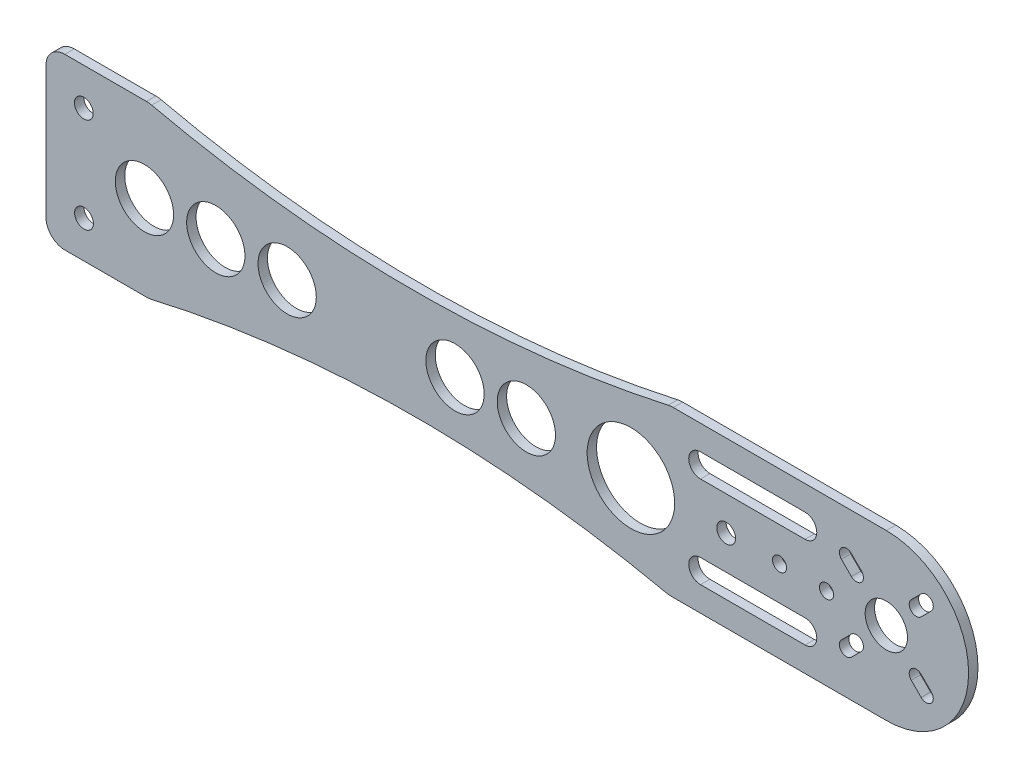
SolidWorks part; units mm, degrees
ref_plane "Alzado" through (0, 0, 0) normal (0, 0, 1) x (1, 0, 0)
ref_plane "Planta" through (0, 0, 0) normal (0, 1, 0) x (1, 0, 0)
ref_plane "Vista lateral" through (0, 0, 0) normal (1, 0, 0) x (0, 0, -1)
sketch "Croquis1" plane through (0, 0, 0) normal (0, 0, 1) x (1, 0, 0)
  line L0 (2814.9766, 1239.0428) -> (2832.3419, 1239.0428)
  line L1 (2814.9766, 1202.994) -> (2832.3207, 1202.994)
  line L2 (2982.2896, 1215.8859) -> (2980.1683, 1213.7646)
  line L3 (2984.411, 1213.7646) -> (2982.2896, 1211.6433)
  line L4 (2995.0176, 1213.7646) -> (2997.1389, 1211.6433)
  line L5 (2997.1389, 1215.8859) -> (2999.2602, 1213.7646)
  line L6 (2997.1389, 1226.4925) -> (2999.2602, 1228.6139)
  line L7 (2995.0176, 1228.6139) -> (2997.1389, 1230.7352)
  line L8 (2984.411, 1228.6139) -> (2982.2896, 1230.7352)
  line L9 (2982.2896, 1226.4925) -> (2980.1683, 1228.6139)
  line L10 (2810.9766, 1235.0428) -> (2810.9766, 1206.994)
  line L11 (2989.7143, 1238.6892) -> (2944.3964, 1238.6892)
  line L12 (2989.7143, 1203.6892) -> (2943.9874, 1203.6892)
  line L13 (2950.1854, 1233.4225) -> (2972.422, 1233.4225)
  line L14 (2950.1854, 1228.4225) -> (2972.422, 1228.4225)
  line L15 (2950.1854, 1208.956) -> (2972.422, 1208.956)
  line L16 (2950.1854, 1213.956) -> (2972.422, 1213.956)
  arc A0 (2810.9766, 1206.994) -> (2814.9766, 1202.994) centre (2814.9766, 1206.994) ccw
  circle A1 centre (2819.0242, 1231.1463) radius 2
  circle A2 centre (2989.7143, 1221.1892) radius 4.5
  arc A3 (2984.411, 1213.7646) -> (2982.2896, 1215.8859) centre (2983.3503, 1214.8253) ccw
  arc A4 (2980.1683, 1213.7646) -> (2982.2896, 1211.6433) centre (2981.229, 1212.704) ccw
  arc A5 (2997.1389, 1215.8859) -> (2995.0176, 1213.7646) centre (2996.0782, 1214.8253) ccw
  arc A6 (2997.1389, 1211.6433) -> (2999.2602, 1213.7646) centre (2998.1995, 1212.704) ccw
  arc A7 (2995.0176, 1228.6139) -> (2997.1389, 1226.4925) centre (2996.0782, 1227.5532) ccw
  arc A8 (2999.2602, 1228.6139) -> (2997.1389, 1230.7352) centre (2998.1995, 1229.6745) ccw
  arc A9 (2982.2896, 1226.4925) -> (2984.411, 1228.6139) centre (2983.3503, 1227.5532) ccw
  arc A10 (2982.2896, 1230.7352) -> (2980.1683, 1228.6139) centre (2981.229, 1229.6745) ccw
  arc A11 (2989.7143, 1203.6892) -> (2989.7143, 1238.6892) centre (2989.7143, 1221.1892) ccw
  arc A12 (2814.9766, 1239.0428) -> (2810.9766, 1235.0428) centre (2814.9766, 1235.0428) ccw
  circle A13 centre (2819.0592, 1210.8908) radius 2
  circle A14 centre (2831.9177, 1221.0235) radius 6.1983
  circle A15 centre (2847.0932, 1221.0395) radius 6.1983
  circle A16 centre (2862.2688, 1221.0554) radius 6.1983
  arc A17 (2833.4549, 1238.9174) -> (2943.3142, 1238.5707) centre (2889.1548, 1482.8664) ccw
  arc A18 (2833.4549, 1238.9174) -> (2832.3419, 1239.0428) centre (2832.3419, 1234.0428) ccw
  arc A19 (2944.3964, 1238.6892) -> (2943.3142, 1238.5707) centre (2944.3964, 1233.6892) ccw
  arc A20 (2942.924, 1203.8036) -> (2833.4449, 1203.122) centre (2889.7046, 959.3015) ccw
  arc A21 (2832.3207, 1202.994) -> (2833.4449, 1203.122) centre (2832.3207, 1207.994) ccw
  arc A22 (2942.924, 1203.8036) -> (2943.9874, 1203.6892) centre (2943.9874, 1208.6892) ccw
  circle A23 centre (2966.9963, 1221.1892) radius 1.5
  circle A24 centre (2976.9963, 1221.1892) radius 1.5
  circle A25 centre (2955.643, 1221.1892) radius 2
  circle A26 centre (2935.3882, 1221.1892) radius 9.3064
  circle A27 centre (2897.9734, 1221.0395) radius 6.1983
  circle A28 centre (2913.1489, 1221.0554) radius 6.1983
  arc A29 (2950.1854, 1233.4225) -> (2950.1854, 1228.4225) centre (2950.1854, 1230.9225) ccw
  arc A30 (2972.422, 1228.4225) -> (2972.422, 1233.4225) centre (2972.422, 1230.9225) ccw
  arc A31 (2950.1854, 1213.956) -> (2950.1854, 1208.956) centre (2950.1854, 1211.456) ccw
  arc A32 (2972.422, 1208.956) -> (2972.422, 1213.956) centre (2972.422, 1211.456) ccw
extrude "Saliente-Extruir1" add sketch "Croquis1" along normal blind 2
